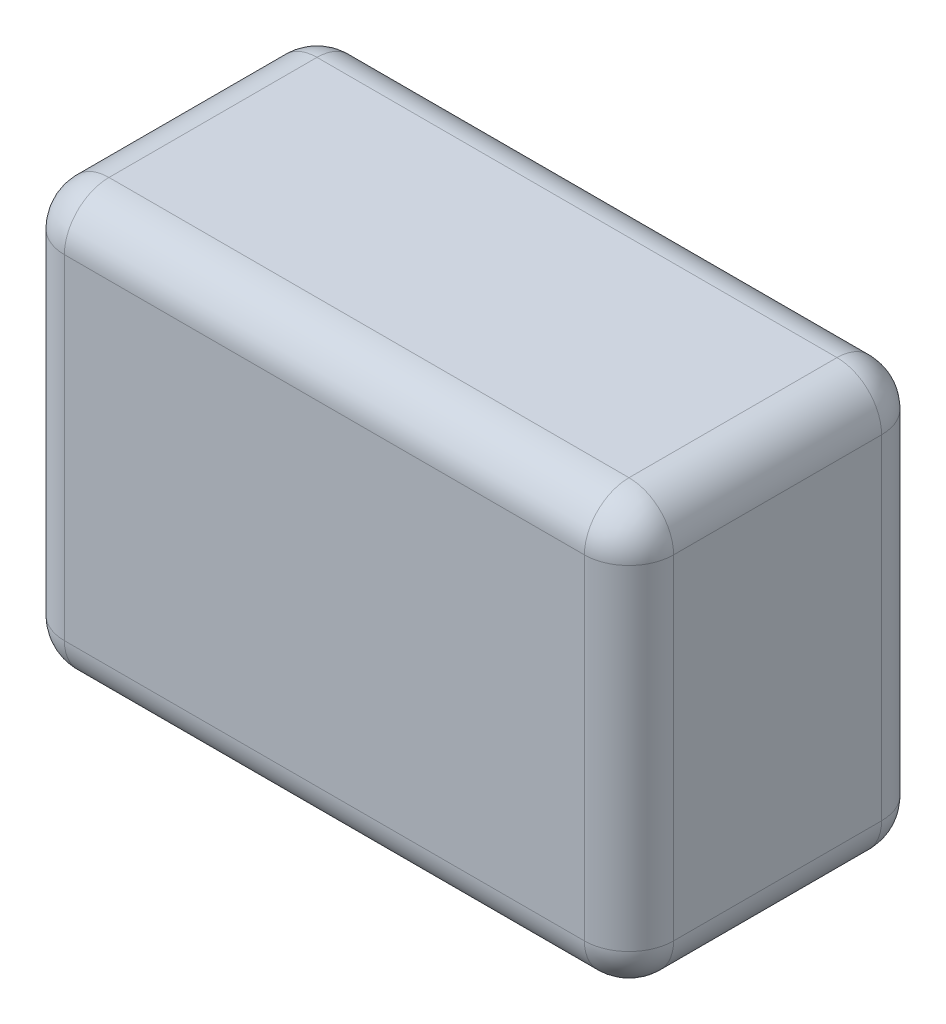
SolidWorks part; units mm, degrees
ref_plane "Front Plane" through (0, 0, 0) normal (0, 0, 1) x (1, 0, 0)
ref_plane "Top Plane" through (0, 0, 0) normal (0, 1, 0) x (1, 0, 0)
ref_plane "Right Plane" through (0, 0, 0) normal (1, 0, 0) x (0, 0, -1)
sketch "Sketch1" plane through (0, 0, 0) normal (0, 1, 0) x (1, 0, 0)
  line L0 (-41, -20) -> (41, 20) construction
  line L1 (-41, 20) -> (41, 20)
  line L2 (-41, 20) -> (-41, -20)
  line L3 (-41, -20) -> (41, -20)
  line L4 (41, 20) -> (41, -20)
  dimension "D1" = 82
  dimension "D2" = 40
extrude "Boss-Extrude1" add sketch "Sketch1" along normal mid plane 57
fillet "Fillet1" radius 6 12 edges at (-41, 0, 20) (41, 0, 20) (41, 0, -20) (-41, 0, -20) (0, 28.5, -20) (41, 28.5, 0) (0, 28.5, 20) (-41, 28.5, 0) (0, -28.5, -20) (41, -28.5, 0) (0, -28.5, 20) (-41, -28.5, 0)
